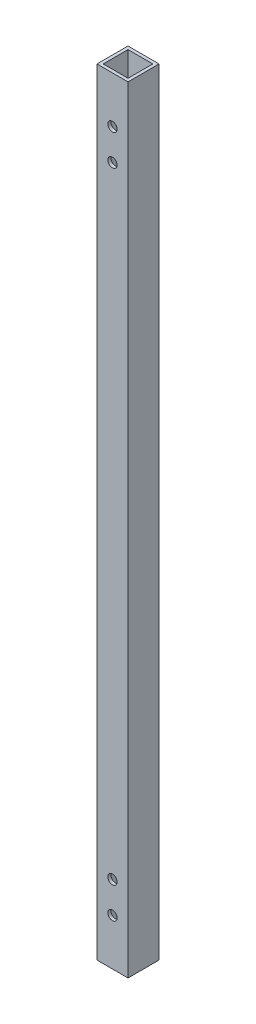
SolidWorks part; units mm, degrees
ref_plane "前视基准面" through (0, 0, 0) normal (0, 0, 1) x (1, 0, 0)
ref_plane "上视基准面" through (0, 0, 0) normal (0, 1, 0) x (1, 0, 0)
ref_plane "右视基准面" through (0, 0, 0) normal (1, 0, 0) x (0, 0, -1)
sketch "草图1" plane through (0, 0, 0) normal (0, 1, 0) x (1, 0, 0)
  line L1 (-5, 5) -> (5, 5)
  line L2 (-5, 5) -> (-5, -5)
  line L3 (-5, -5) -> (5, -5)
  line L4 (5, 5) -> (5, -5)
  line L5 (-5, 5) -> (5, -5) construction
  line L6 (-5, -5) -> (5, 5) construction
  line L7 (-4, 4) -> (4, 4)
  line L8 (-4, 4) -> (-4, -4)
  line L9 (-4, -4) -> (4, -4)
  line L10 (4, 4) -> (4, -4)
  line L11 (-4, 4) -> (4, -4) construction
  line L12 (-4, -4) -> (4, 4) construction
  point P0 (0, 0)
  point P6 (0, 0)
extrude "凸台-拉伸1" add sketch "草图1" along normal blind 250
hole_wizard "Ø3.0 (3) 直径孔1" positions "草图3" profile "草图2" hole size "Ø3.0" standard "GB" end condition through all
sketch "草图3" plane through (0, 0, 5) normal (0, 0, 1) x (1, 0, 0)
  line L0 (0, 0) -> (0, 25)
  line L1 (-5, 0) -> (5, 0) construction
  line L3 (0, 15) -> (0, 0)
  point P0 (0, 15)
  point P2 (0, 25)
sketch "草图2" plane through (0, 15, 5) normal (1, 0, 0) x (0, -1, 0)
  line L0 (0, 0) -> (0, 10)
  line L1 (0, 10) -> (1.5, 10)
  line L2 (1.5, 10) -> (1.5, 0)
  line L5 (1.5, 0) -> (0, 0)
  line L11 (0, -6.35) -> (0, 107.95) construction
  dimension "通孔孔直径" = 3
  dimension "通孔孔深度" = 10
ref_plane "基准面1" through (0, 125, 0) normal (0, -1, 0) x (-1, 0, 0)
mirror "镜向1" about plane through (0, 125, 0) normal (0, -1, 0) of "Ø3.0 (3) 直径孔1"
